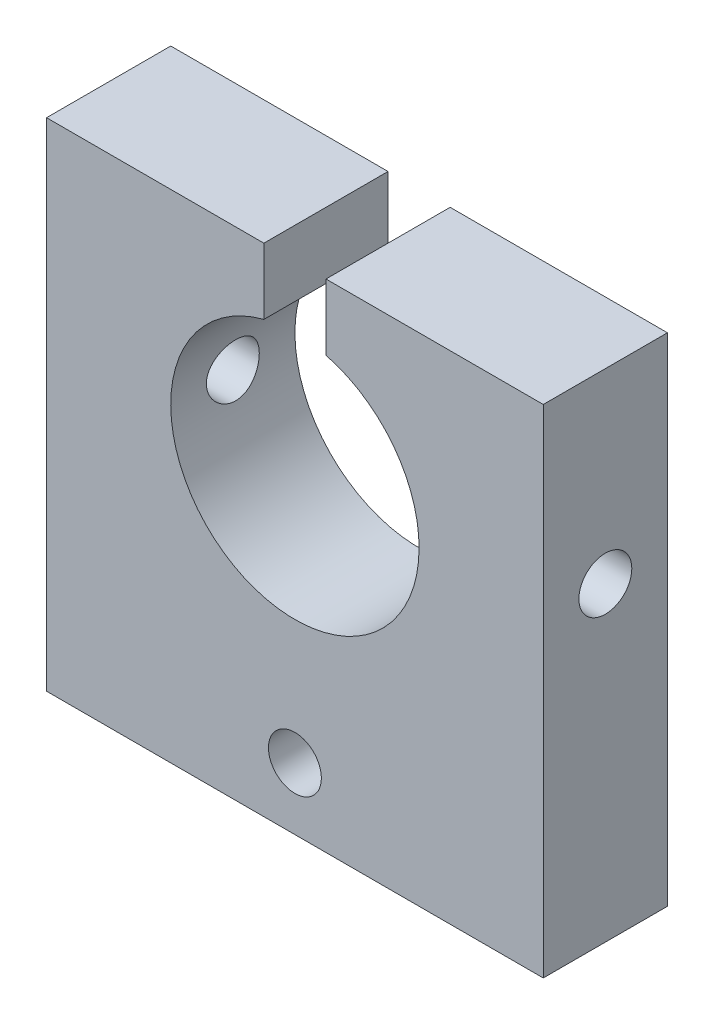
SolidWorks part; units mm, degrees
material "6061 Alloy"
ref_plane "Front Plane" through (0, 0, 0) normal (0, 0, 1) x (1, 0, 0)
ref_plane "Top Plane" through (0, 0, 0) normal (0, 1, 0) x (1, 0, 0)
ref_plane "Right Plane" through (0, 0, 0) normal (1, 0, 0) x (0, 0, -1)
sketch "Sketch1" plane through (0, 0, 0) normal (0, 0, 1) x (1, 0, 0)
  line L1 (-12.7, -12.7) -> (12.7, -12.7)
  line L2 (-12.7, -12.7) -> (-12.7, 12.7)
  line L3 (-12.7, 12.7) -> (12.7, 12.7)
  line L4 (12.7, -12.7) -> (12.7, 12.7)
  line L5 (-12.7, -12.7) -> (12.7, 12.7) construction
  line L6 (-12.7, 12.7) -> (12.7, -12.7) construction
  point P0 (0, 0)
  dimension "D1" = 25.4
  dimension "D2" = 25.4
extrude "Boss-Extrude1" add sketch "Sketch1" along normal blind 6.35
sketch "Sketch2" plane through (0, 0, 6.35) normal (0, 0, 1) x (1, 0, 0)
  line L1 (-1.5875, 1.7402) -> (1.5875, 1.7402)
  line L2 (-1.5875, 1.7402) -> (-1.5875, 12.7)
  line L3 (-1.5875, 12.7) -> (1.5875, 12.7)
  line L4 (1.5875, 1.7402) -> (1.5875, 12.7)
  line L5 (12.7, 12.7) -> (-12.7, 12.7) construction
  circle A0 centre (0, 3.175) radius 6.35
  line M4 (12.7, 12.7) -> (-12.7, 12.7)
  dimension "D2" = 12.7
  dimension "D1" = 3.175
  dimension "D3" = 1.5875
  dimension "D4" = 3.175
  dimension "D5" = 0
  dimension "D6" = 0
extrude "Cut-Extrude1" cut sketch "Sketch2" against normal through all contours L2 A0 L4 L1 | L4 A0 L2 L1 | A0 L4 L2 M4
hole_wizard "#6-32 Tapped Hole1" positions "Sketch4" profile "Sketch5" tap size "#6-32" standard "ANSI Inch" end condition through all
sketch "Sketch4" plane through (12.7, 0, 0) normal (1, 0, 0) x (0, 0, -1)
  line L0 (-6.35, -12.7) -> (-6.35, 12.7) construction
  line L1 (-6.35, 12.7) -> (0, 12.7) construction
  point P0 (-3.175, 3.175)
  dimension "D1" = 3.175
  dimension "D2" = 9.525
sketch "Sketch5" plane through (12.7, 3.175, 3.175) normal (0, 1, 0) x (0, 0, -1)
  line L0 (0, 0) -> (0, 25.4)
  line L1 (0, 25.4) -> (1.3525, 25.4)
  line L2 (1.3525, 25.4) -> (1.3525, 0)
  line L5 (1.3525, 0) -> (0, 0)
  line L11 (0, -6.35) -> (0, 107.95) construction
  dimension "Thru Tap Drill Dia." = 2.7051
  dimension "Thru Tap Drill Depth" = 25.4
cosmetic thread "Hole Thread1" parameters "D2"=3.5052
hole_wizard "#6-32 Tapped Hole2" positions "Sketch6" profile "Sketch7" tap size "#6-32" standard "ANSI Inch" end condition up to next
sketch "Sketch6" plane through (0, 0, 6.35) normal (0, 0, 1) x (1, 0, 0)
  line L0 (-12.7, -12.7) -> (12.7, -12.7) construction
  point P0 (0, -9.525)
  dimension "D1" = 3.175
sketch "Sketch7" plane through (0, -9.525, 6.35) normal (1, 0, 0) x (0, -1, 0)
  line L0 (0, 0) -> (0, 6.35)
  line L1 (0, 6.35) -> (1.3525, 6.35)
  line L2 (1.3525, 6.35) -> (1.3525, 0)
  line L5 (1.3525, 0) -> (0, 0)
  line L11 (0, -6.35) -> (0, 107.95) construction
  dimension "Thru Tap Drill Dia." = 2.7051
  dimension "Thru Tap Drill Depth" = 6.35
cosmetic thread "Hole Thread2" parameters "D2"=3.5052
